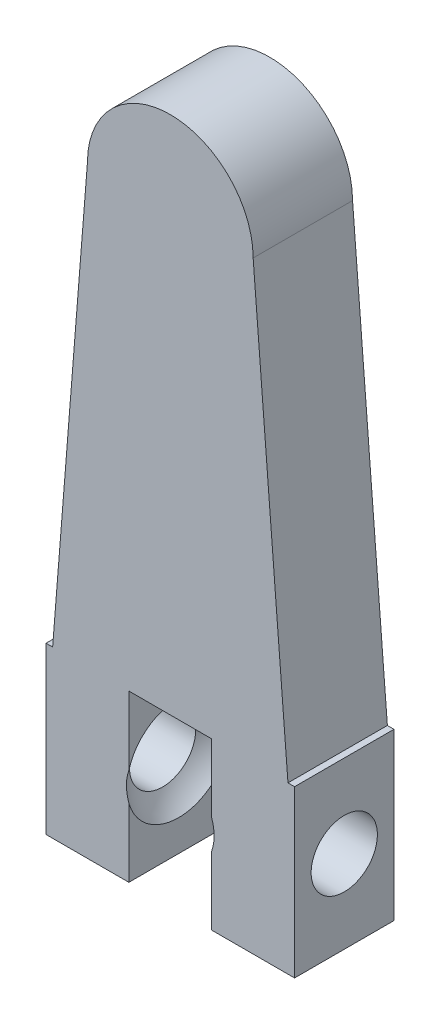
SolidWorks part; units mm, degrees
ref_plane "Alzado" through (0, 0, 0) normal (0, 0, 1) x (1, 0, 0)
ref_plane "Planta" through (0, 0, 0) normal (0, 1, 0) x (1, 0, 0)
ref_plane "Vista lateral" through (0, 0, 0) normal (1, 0, 0) x (0, 0, -1)
sketch "Croquis1" plane through (0, 0, 0) normal (0, 0, 1) x (1, 0, 0)
  line L0 (0, 0) -> (0, -31.383) construction
  line L1 (0, -31.383) -> (7.5, -31.383) construction
  line L2 (0, -31.383) -> (0, -36.383) construction
  line L3 (0, -31.383) -> (-7.5, -31.383) construction
  line L4 (7.5, -36.383) -> (2.5, -36.383)
  line L5 (7.5, -36.383) -> (7.5, -26.383)
  line L6 (7.5, -26.383) -> (7.1017, -26.383)
  line L7 (2.5, -36.383) -> (2.5, -26.383)
  line L8 (-7.1017, -26.383) -> (-5, 0)
  line L9 (-7.5, -36.383) -> (-2.5, -36.383)
  line L10 (-7.5, -36.383) -> (-7.5, -26.383)
  line L11 (-7.5, -26.383) -> (-7.1017, -26.383)
  line L12 (-2.5, -36.383) -> (-2.5, -26.383)
  line L13 (7.1017, -26.383) -> (5, 0)
  line L14 (2.5, -26.383) -> (-2.5, -26.383)
  circle A0 centre (0, 0) radius 4 construction
  arc A1 (5, 0) -> (-5, 0) centre (0, 0) ccw
  dimension "D2" = 8
  dimension "D3" = 7.5
  dimension "D1" = 31.383
  dimension "D4" = 7.5
  dimension "D5" = 10
  dimension "D6" = 10
  dimension "D7" = 5
  dimension "D8" = 5
extrude "Saliente-Extruir1" add sketch "Croquis1" along normal blind 6
sketch "Croquis2" plane through (0, 0, 0) normal (1, 0, 0) x (0, 0, -1)
  line L1 (-6, 0) -> (0, 0) construction
  line L2 (3, 0) -> (-5, 0)
  arc A0 (3, 0) -> (-5, 0) centre (-1, 0) ccw
revolve "Cortar-Revolución1" cut sketch "Croquis2" angle 360 about L2
sketch "Croquis4" plane through (7.5, 0, 0) normal (1, 0, 0) x (0, 0, -1)
  line L0 (-3, -26.383) -> (-3, -36.383) construction
  line L1 (-6, -26.383) -> (0, -26.383) construction
  line L2 (-6, -36.383) -> (0, -36.383) construction
  circle A0 centre (-3, -31.383) radius 2
extrude "Cortar-Extruir1" cut sketch "Croquis4" along direction (1, 0, 0) on the side against the normal blind 15
sketch "Croquis5" plane through (0, 0, 0) normal (1, 0, 0) x (0, 0, -1)
  line L6 (-7, -31.383) -> (1, -31.383)
  arc A0 (1, -31.383) -> (-7, -31.383) centre (-3, -31.383) ccw
revolve "Cortar-Revolución2" cut sketch "Croquis5" angle 360 about L6
